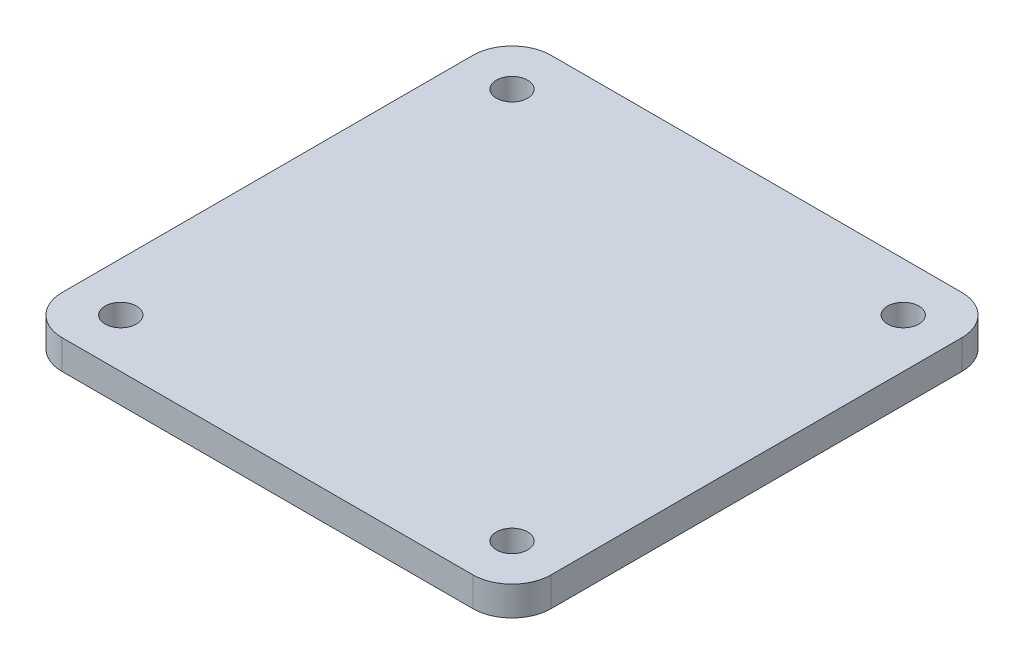
SolidWorks part; units mm, degrees
ref_plane "Front Plane" through (0, 0, 0) normal (0, 0, 1) x (1, 0, 0)
ref_plane "Top Plane" through (0, 0, 0) normal (0, 1, 0) x (1, 0, 0)
ref_plane "Right Plane" through (0, 0, 0) normal (1, 0, 0) x (0, 0, -1)
sketch "Sketch1" plane through (0, 0, 0) normal (0, 1, 0) x (1, 0, 0)
  line L1 (-25, -25) -> (25, -25)
  line L2 (-25, -25) -> (-25, 25)
  line L3 (-25, 25) -> (25, 25)
  line L4 (25, -25) -> (25, 25)
  line L5 (-25, -25) -> (25, 25) construction
  line L6 (-25, 25) -> (25, -25) construction
  point P0 (0, 0)
  dimension "D1" = 50
  dimension "D2" = 50
extrude "Boss-Extrude1" add sketch "Sketch1" along normal blind 3
sketch "Sketch2" plane through (0, 3, 0) normal (0, 1, 0) x (1, 0, 0)
  line L1 (-20, -20) -> (20, -20) construction
  line L2 (-20, -20) -> (-20, 20) construction
  line L3 (-20, 20) -> (20, 20) construction
  line L4 (20, -20) -> (20, 20) construction
  line L5 (-20, -20) -> (20, 20) construction
  line L6 (-20, 20) -> (20, -20) construction
  circle A0 centre (-20, 20) radius 1.6
  circle A1 centre (20, 20) radius 1.6
  circle A2 centre (20, -20) radius 1.6
  circle A3 centre (-20, -20) radius 1.6
  point P0 (0, 0)
  dimension "D2" = 3.2
  dimension "D1" = 40
extrude "Cut-Extrude1" cut sketch "Sketch2" against normal up to surface (3 mm away) up to face at (0, 0, 0)
fillet "Fillet1" radius 4 4 edges at (25, 1.5, 25) (25, 1.5, -25) (-25, 1.5, 25) (-25, 1.5, -25)
